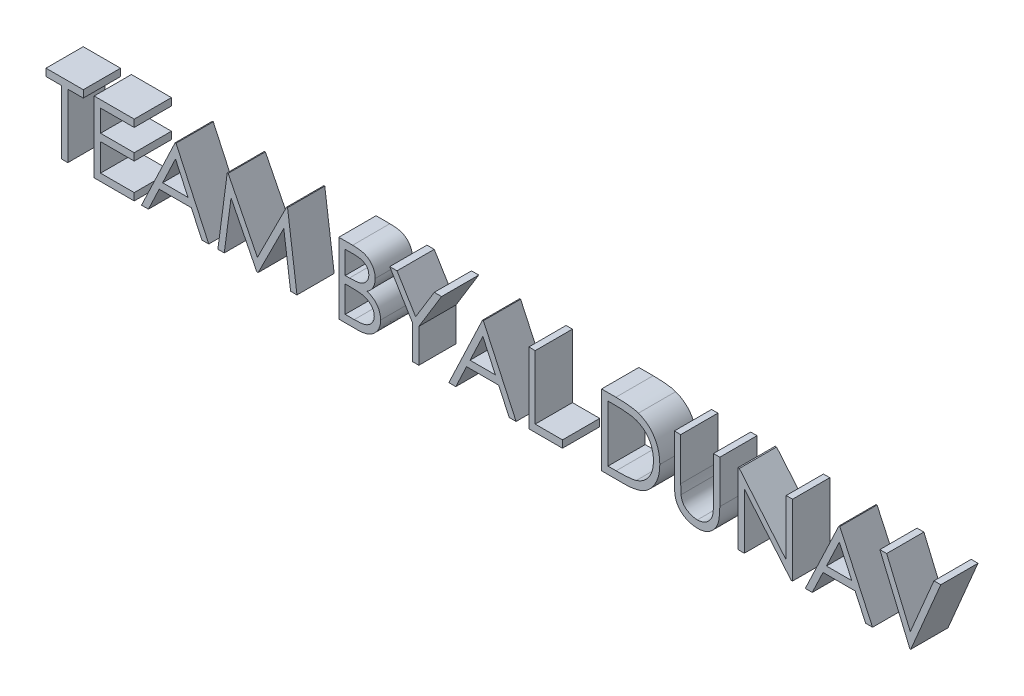
SolidWorks part; units mm, degrees
ref_plane "Front Plane" through (0, 0, 0) normal (0, 0, 1) x (1, 0, 0)
ref_plane "Top Plane" through (0, 0, 0) normal (0, 1, 0) x (1, 0, 0)
ref_plane "Right Plane" through (0, 0, 0) normal (1, 0, 0) x (0, 0, -1)
sketch "Sketch1" plane through (0, 0, 0) normal (0, 0, 1) x (1, 0, 0)
  line L0 (-128.1927, -21.24) -> (135.4579, -21.24) construction
  text T0 "TEAM BYAL DUNAV" font "Century Gothic" height in points 72
  point P0 (0, 0)
extrude "Boss-Extrude3" add sketch "Sketch1" along normal blind 10
